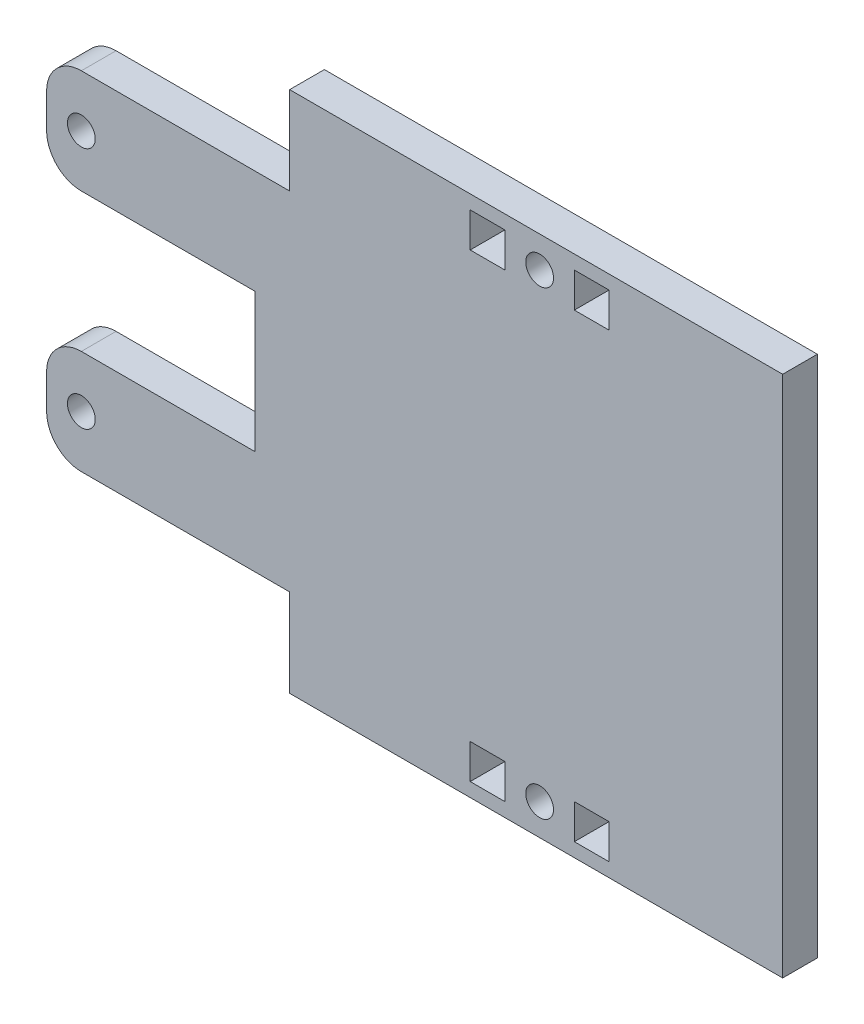
SolidWorks part; units mm, degrees
ref_plane "Plan de face" through (0, 0, 0) normal (0, 0, 1) x (1, 0, 0)
ref_plane "Plan de dessus" through (0, 0, 0) normal (0, 1, 0) x (1, 0, 0)
ref_plane "Plan de droite" through (0, 0, 0) normal (1, 0, 0) x (0, 0, -1)
sketch "Esquisse1" plane through (0, 0, 0) normal (0, 0, 1) x (1, 0, 0)
  line L0 (0, 0) -> (71, 0) construction
  line L1 (0, 37.65) -> (71, 37.65)
  line L2 (71, 37.65) -> (71, -37.65)
  line L3 (0, 37.65) -> (0, -37.65) construction
  line L4 (0, -37.65) -> (71, -37.65)
  line L5 (0, -37.65) -> (0, -25)
  line L6 (0, -25) -> (-35, -25)
  line L7 (-35, -25) -> (-35, -10)
  line L8 (-35, -10) -> (-5, -10)
  line L9 (-5, -10) -> (-5, 10)
  line L10 (-5, 10) -> (-35, 10)
  line L11 (-35, 10) -> (-35, 25)
  line L12 (-35, 25) -> (0, 25)
  line L13 (0, 25) -> (0, 37.65)
  line L14 (-35, 17.5) -> (0, 17.5) construction
  circle A0 centre (-30, 17.5) radius 2
  circle A1 centre (-30, -17.5) radius 2
  line B0 (31, 33.15) -> (41, 33.15) construction
  line B1 (31, 35.65) -> (26, 35.65)
  line B2 (31, 35.65) -> (31, 30.65)
  line B3 (31, 30.65) -> (26, 30.65)
  line B4 (26, 35.65) -> (26, 30.65)
  line B5 (41, 35.65) -> (46, 35.65)
  line B6 (41, 35.65) -> (41, 30.65)
  line B7 (41, 30.65) -> (46, 30.65)
  line B8 (46, 35.65) -> (46, 30.65)
  line B9 (36, 33.15) -> (36, 40.1224) construction
  circle B10 centre (36, 33.15) radius 2
  line B11 (31, -35.65) -> (26, -35.65)
  line B12 (31, -35.65) -> (31, -30.65)
  line B13 (31, -30.65) -> (26, -30.65)
  line B14 (26, -35.65) -> (26, -30.65)
  line B15 (41, -35.65) -> (46, -35.65)
  line B16 (41, -35.65) -> (41, -30.65)
  line B17 (41, -30.65) -> (46, -30.65)
  line B18 (46, -35.65) -> (46, -30.65)
  line B19 (36, -33.15) -> (36, -40.1224) construction
  circle B20 centre (36, -33.15) radius 2
  dimension "D8" = 4
  dimension "D1" = 36
  dimension "D2" = 20
  dimension "D3" = 2
  dimension "D4" = 71
  dimension "D5" = 33.15
  dimension "D6" = 20
  dimension "D7" = 15
  dimension "D9" = 25
  dimension "D10" = 30
  dimension "D11" = 5
sketch_block_instance "Trou M4 plots 5mm-1"
sketch_block "Trou M4 plots 5mm" parameters "D2"=4, "D1"=5, "D3"=5, "D4"=10
sketch_block_instance "Trou M4 plots 5mm-5"
extrude "Boss.-Extru.1" add sketch "Esquisse1" along normal blind 5
fillet "Congé1" radius 5 4 edges at (-35, -25, 2.5) (-35, -10, 2.5) (-35, 10, 2.5) (-35, 25, 2.5)
